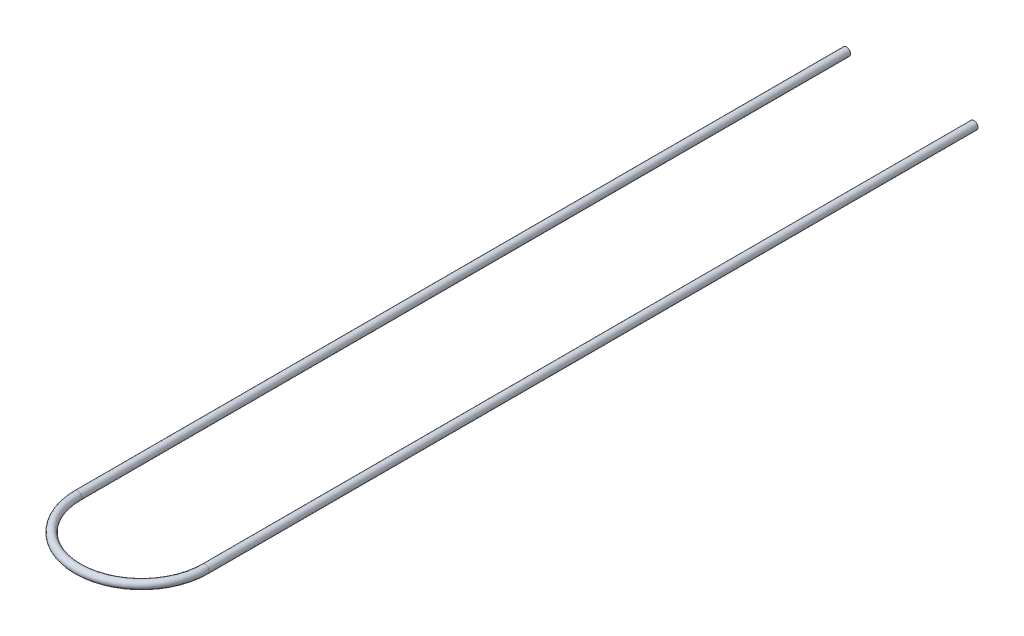
SolidWorks part; units mm, degrees
ref_plane "Front Plane" through (0, 0, 0) normal (0, 0, 1) x (1, 0, 0)
ref_plane "Top Plane" through (0, 0, 0) normal (0, 1, 0) x (1, 0, 0)
ref_plane "Right Plane" through (0, 0, 0) normal (1, 0, 0) x (0, 0, -1)
sketch "Sketch1" plane through (0, 0, 0) normal (0, 1, 0) x (1, 0, 0)
  line L0 (314.77, -300) -> (314.77, -2440)
  line L2 (-40, -300) -> (-40, -2440)
  arc A0 (-40, -2440) -> (314.77, -2440) centre (137.385, -2440) ccw
  dimension "D1" = 2140
  dimension "D2" = 354.77
ref_plane "Plane1" through (314.77, 0, 300) normal (0, 0, -1) x (-1, 0, 0)
sketch "Sketch2" plane through (314.77, 0, 300) normal (0, 0, -1) x (-1, 0, 0)
  circle A0 centre (0, 0) radius 9.95
  circle A1 centre (0, 0) radius 11.1
  dimension "D1" = 22.2
  dimension "D2" = 19.9
sweep "Sweep1" add profiles "Sketch2" path "Sketch1"
